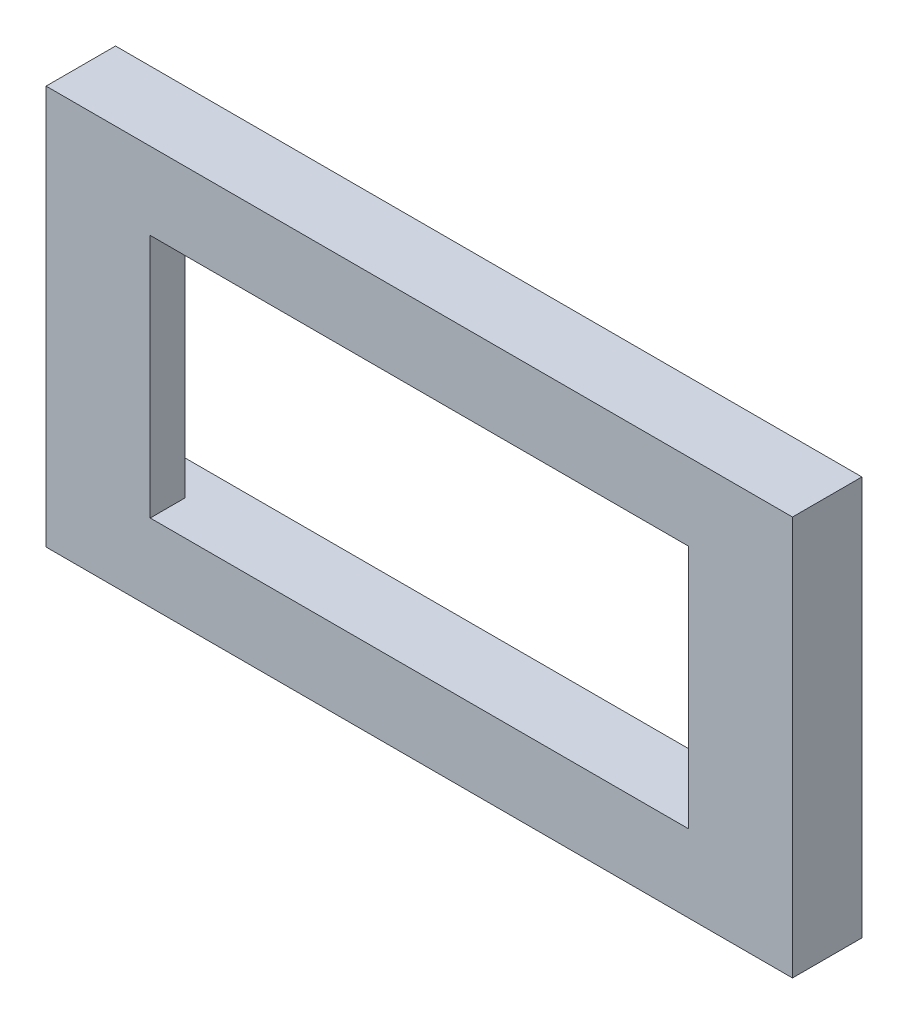
SolidWorks part; units mm, degrees
ref_plane "Front Plane" through (0, 0, 0) normal (0, 0, 1) x (1, 0, 0)
ref_plane "Top Plane" through (0, 0, 0) normal (0, 1, 0) x (1, 0, 0)
ref_plane "Right Plane" through (0, 0, 0) normal (1, 0, 0) x (0, 0, -1)
sketch "Sketch1" plane through (0, 0, 0) normal (0, 0, 1) x (1, 0, 0)
  line L1 (0, 0) -> (43, 0)
  line L2 (0, 0) -> (0, 23)
  line L3 (0, 23) -> (43, 23)
  line L4 (43, 0) -> (43, 23)
  line L5 (4, 18.55) -> (39, 18.55)
  line L6 (4, 18.55) -> (4, 4.45)
  line L7 (4, 4.45) -> (39, 4.45)
  line L8 (39, 18.55) -> (39, 4.45)
  point P9 (4, 11.5)
  point P10 (0, 11.5)
  point P11 (21.5, 0)
  point P12 (21.5, 4.45)
  dimension "D1" = 35
  dimension "D2" = 14.1
  dimension "D3" = 23
  dimension "D4" = 43
extrude "Boss-Extrude1" add sketch "Sketch1" along normal blind 2
sketch "Sketch2" plane through (0, 0, 2) normal (0, 0, 1) x (1, 0, 0)
  line L20 (39, 18.55) -> (4, 18.55) construction
  line L21 (37, 18.55) -> (6, 18.55)
  line L22 (4, 4.45) -> (39, 4.45) construction
  line L23 (6, 4.45) -> (37, 4.45)
  line L24 (37, 6.45) -> (37, 16.55)
  line L25 (37, 16.55) -> (6, 16.55)
  line L26 (6, 16.55) -> (6, 6.45)
  line L27 (6, 6.45) -> (37, 6.45)
  line L28 (37, 4.45) -> (37, 18.55)
  line L30 (6, 18.55) -> (6, 4.45)
  line L36 (0, 23) -> (0, 0)
  line L37 (0, 0) -> (43, 0)
  line L38 (43, 0) -> (43, 23)
  line L39 (43, 23) -> (0, 23)
  line L40 (0, 23) -> (0, 0)
  line L41 (0, 0) -> (43, 0)
  line L42 (43, 0) -> (43, 23)
  line L43 (43, 23) -> (0, 23)
  point P0 (6, 18.55)
  dimension "D1" = 0
  dimension "D2" = 2
extrude "Boss-Extrude2" add sketch "Sketch2" along normal blind 2
